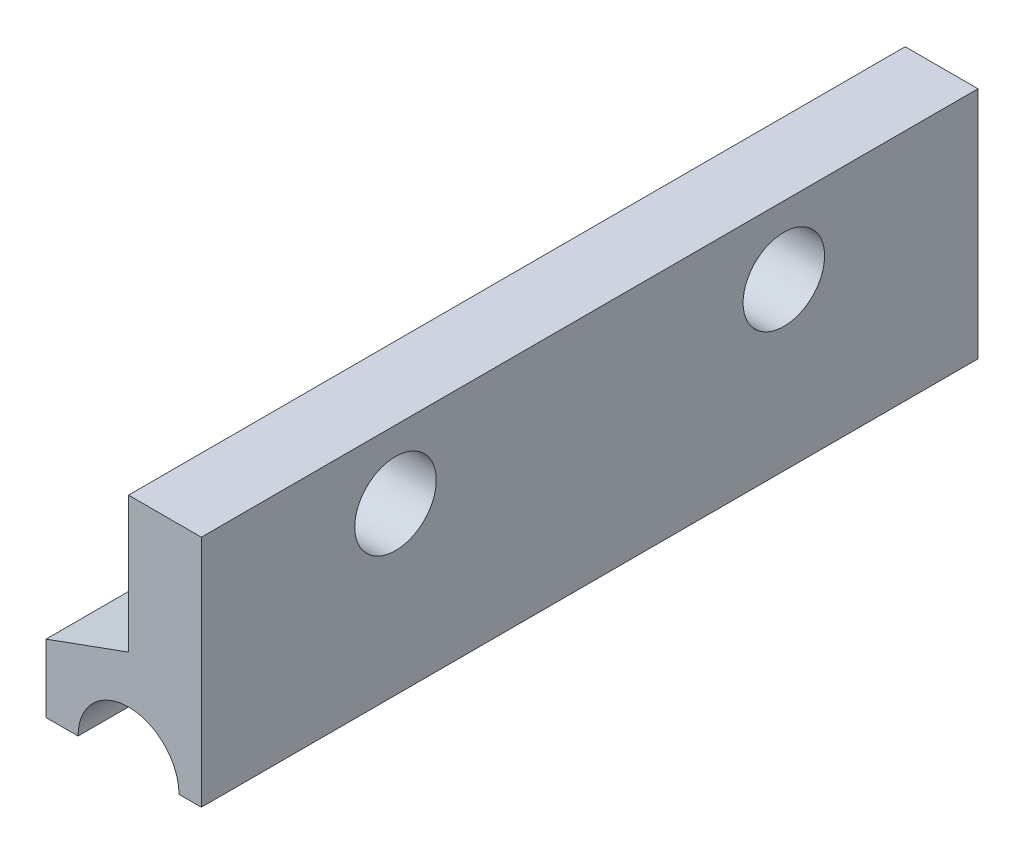
SolidWorks part; units mm, degrees
material "PET"
ref_plane "Front Plane" through (0, 0, 0) normal (0, 0, 1) x (1, 0, 0)
ref_plane "Top Plane" through (0, 0, 0) normal (0, 1, 0) x (1, 0, 0)
ref_plane "Right Plane" through (0, 0, 0) normal (1, 0, 0) x (0, 0, -1)
sketch "Sketch1" plane through (0, 0, 0) normal (0, 0, 1) x (1, 0, 0)
  line L0 (-2.6, 0) -> (-4.25, 0)
  line L1 (-4.25, 0) -> (-4.25, 3.5)
  line L2 (-4.25, 3.5) -> (0, 5.0469)
  line L3 (0, 5.0469) -> (0, 12.0469)
  line L4 (0, 12.0469) -> (3.75, 12.0469)
  line L5 (3.75, 12.0469) -> (3.75, 0)
  line L6 (3.75, 0) -> (2.6, 0)
  arc A0 (2.6, 0) -> (-2.6, 0) centre (0, 0) ccw
  dimension "D1" = 5.2
  dimension "D2" = 1.15
  dimension "D3" = 3.5
  dimension "D4" = 110
  dimension "D5" = 8
  dimension "D6" = 7
extrude "Boss-Extrude1" add sketch "Sketch1" along normal blind 40
sketch "Sketch2" plane through (0, 0, 0) normal (-1, 0, 0) x (0, 0, 1)
  line L0 (0, 8.5469) -> (40, 8.5469) construction
  line L1 (0, 12.0469) -> (0, 5.0469) construction
  line L2 (40, 12.0469) -> (40, 5.0469) construction
  circle A0 centre (10, 8.5469) radius 2.1
  circle A1 centre (30, 8.5469) radius 2.1
  dimension "D1" = 4.2
  dimension "D2" = 10
  dimension "D3" = 4.2
  dimension "D4" = 10
extrude "Cut-Extrude1" cut sketch "Sketch2" against normal through all
